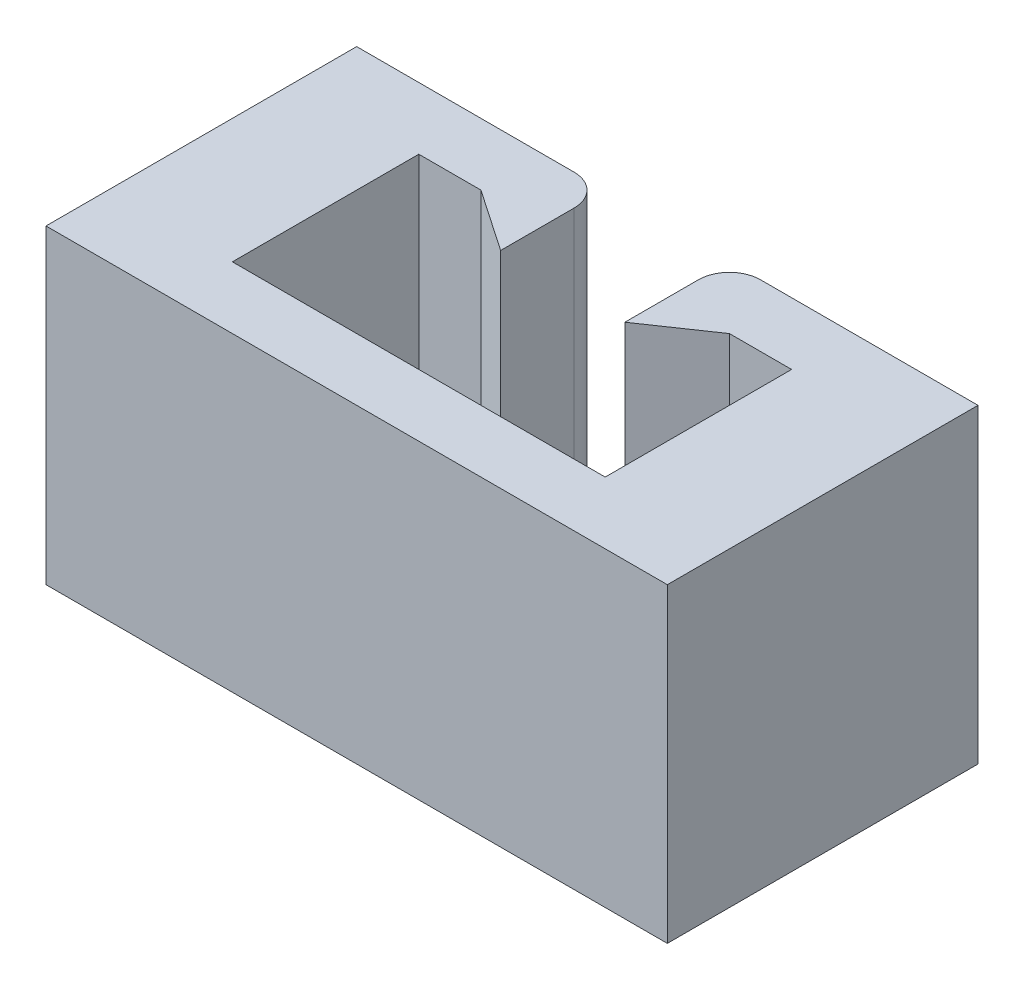
SolidWorks part; units mm, degrees
ref_plane "Front Plane" through (0, 0, 0) normal (0, 0, 1) x (1, 0, 0)
ref_plane "Top Plane" through (0, 0, 0) normal (0, 1, 0) x (1, 0, 0)
ref_plane "Right Plane" through (0, 0, 0) normal (1, 0, 0) x (0, 0, -1)
sketch "Sketch1" plane through (0, 0, 0) normal (0, 1, 0) x (1, 0, 0)
  line L0 (1, 1.5) -> (1, 0.8171)
  line L1 (-5, -2.5) -> (5, -2.5)
  line L2 (-5, -2.5) -> (-5, 2.5)
  line L3 (-5, 2.5) -> (-1.5, 2.5)
  line L4 (5, -2.5) -> (5, 2.5)
  line L5 (-5, -2.5) -> (5, 2.5) construction
  line L6 (-5, 2.5) -> (5, -2.5) construction
  line L7 (-3, 1.5) -> (-2, 1.5)
  line L8 (-3, 1.5) -> (-3, -1.5)
  line L9 (-3, -1.5) -> (3, -1.5)
  line L10 (3, 1.5) -> (3, -1.5)
  line L11 (-3, 1.5) -> (3, -1.5) construction
  line L12 (-3, -1.5) -> (3, 1.5) construction
  line L13 (-1, 1.5) -> (-1, 2)
  line L14 (1, 1.5) -> (1, 2)
  line L15 (1.5, 2.5) -> (5, 2.5)
  line L16 (2, 1.5) -> (3, 1.5)
  line L17 (-1, 1.5) -> (-1, 0.8171)
  line L18 (-1, 0.8171) -> (-2, 1.5)
  line L20 (1, 0.8171) -> (2, 1.5)
  arc A0 (1.5, 2.5) -> (1, 2) centre (1.5, 2) ccw
  arc A1 (-1, 2) -> (-1.5, 2.5) centre (-1.5, 2) ccw
  point P0 (0, 0)
  point P5 (0, 0)
  dimension "D4" = 0.5
  dimension "D1" = 10
  dimension "D2" = 5
  dimension "D3" = 1
  dimension "D5" = 1
  dimension "D6" = 1
extrude "Boss-Extrude1" add sketch "Sketch1" along normal blind 5
